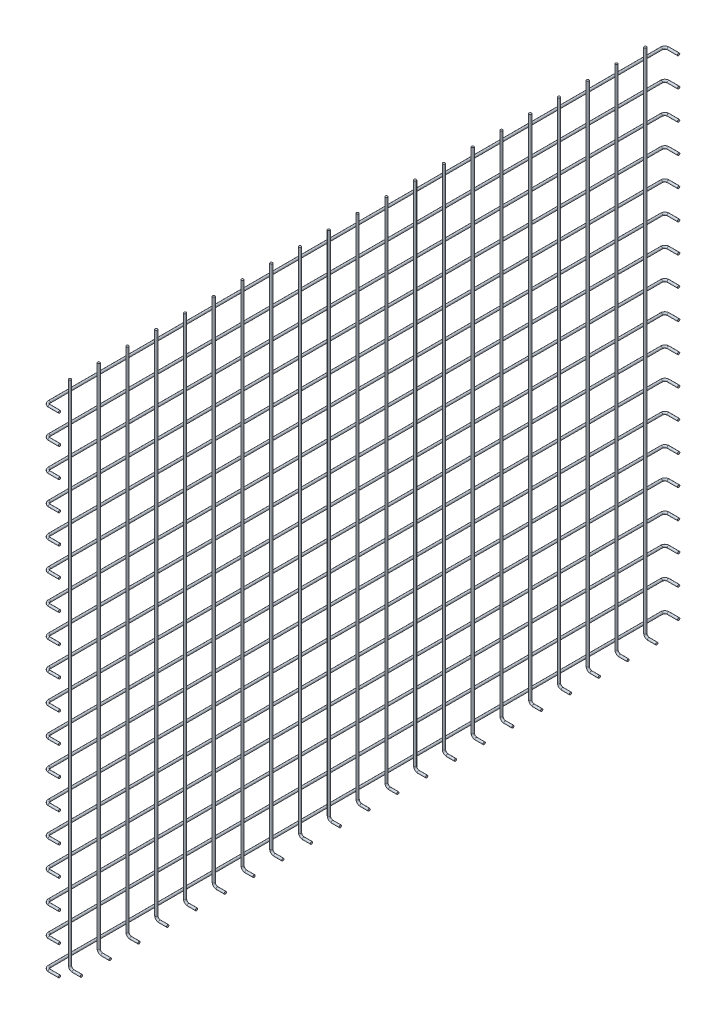
SolidWorks part; units mm, degrees
material "AISI 1020"
ref_plane "Спереди" through (0, 0, 0) normal (0, 0, 1) x (1, 0, 0)
ref_plane "Сверху" through (0, 0, 0) normal (0, 1, 0) x (1, 0, 0)
ref_plane "Справа" through (0, 0, 0) normal (1, 0, 0) x (0, 0, -1)
sketch "Эскиз1" plane through (0, 0, 0) normal (0, 0, 1) x (1, 0, 0)
  line L0 (20, 2) -> (6, 2)
  line L1 (20, -50) -> (20, 2650.6738) construction
  line L2 (0, 8) -> (0, 890)
  line L3 (-6, 875) -> (-1.25, 875) construction
  line L4 (22, 0) -> (-22, 0) construction
  arc A0 (6, 2) -> (0, 8) centre (6, 8) cw
  point P4 (0, 295.6989)
  point P7 (0, 822.7435)
  point P8 (0, 878.9157)
  point P11 (13, 2)
  dimension "D3" = 6
  dimension "D1" = 15
  dimension "D2" = 2
ref_plane "Плоскость1" through (20, 0, 0) normal (1, 0, 0) x (0, 0, -1)
sketch "Эскиз2" plane through (20, 0, 0) normal (1, 0, 0) x (0, 0, -1)
  circle A0 centre (0, 2) radius 2
  dimension "D1" = 4
sweep "По траектории1" add profiles "Эскиз2" path "Эскиз1"
pattern_linear "Линейный массив2" count 11 spacing 50 along (0, 0, -1) of bodies 103
pattern_linear "Линейный массив3" count 11 spacing 50 along (0, 0, 1) of bodies 103
ref_plane "Плоскость2" through (0, 20, 0) normal (0, 1, 0) x (1, 0, 0)
sketch "Эскиз3" plane through (0, 20, 0) normal (0, 1, 0) x (1, 0, 0)
  line L0 (20, 538) -> (2, 538)
  line L1 (2, -538) -> (20, -538)
  line L2 (-4, -532) -> (-4, 532)
  line L3 (20, 700.1025) -> (20, -1090) construction
  line L4 (-22, 540) -> (22, 540) construction
  line L5 (-22, -540) -> (22, -540) construction
  circle A0 centre (0, 500) radius 2 construction
  arc A1 (2, 538) -> (-4, 532) centre (2, 532) ccw
  arc A2 (2, -538) -> (-4, -532) centre (2, -532) cw
  point P6 (0, 0)
  point P11 (0, 0)
  dimension "D1" = 2
  dimension "D4" = 6
  dimension "D2" = 2
  dimension "D3" = 2
sketch "Эскиз4" plane through (20, 0, 0) normal (1, 0, 0) x (0, 0, -1)
  circle A0 centre (538, 20) radius 2
  dimension "D1" = 4
sweep "По траектории2" add profiles "Эскиз4" path "Эскиз3"
pattern_linear "Линейный массив4" count 18 spacing 50 along (0, 1, 0) of "По траектории2"
